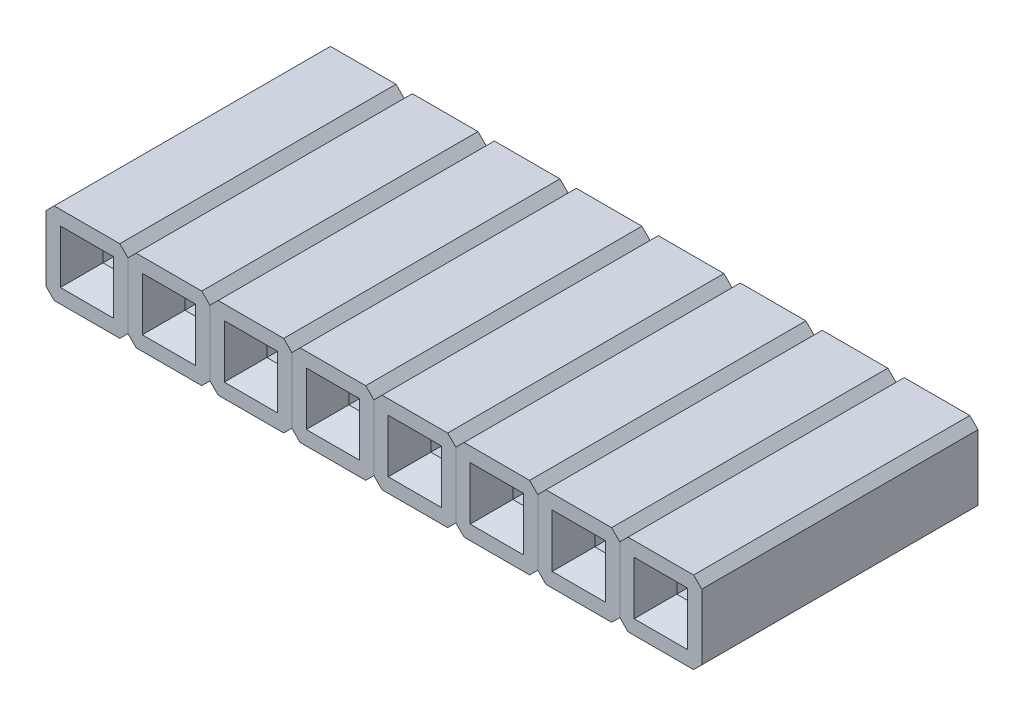
SolidWorks part; units mm, degrees
ref_plane "Front Plane" through (0, 0, 0) normal (0, 0, 1) x (1, 0, 0)
ref_plane "Top Plane" through (0, 0, 0) normal (0, 1, 0) x (1, 0, 0)
ref_plane "Right Plane" through (0, 0, 0) normal (1, 0, 0) x (0, 0, -1)
sketch "Sketch1" plane through (0, 0, 0) normal (0, 0, 1) x (1, 0, 0)
  line L1 (0, 0) -> (2.54, 0)
  line L2 (0, 0) -> (0, 2.54)
  line L3 (0, 2.54) -> (2.54, 2.54)
  line L4 (2.54, 0) -> (2.54, 2.54)
  dimension "D1" = 2.54
  dimension "D2" = 2.54
extrude "Boss-Extrude1" add sketch "Sketch1" along normal blind 8.5598
sketch "Sketch2" plane through (0, 0, 8.5598) normal (0, 0, 1) x (1, 0, 0)
  line L0 (0, 1.27) -> (2.54, 1.27) construction
  line L1 (0, 2.54) -> (0, 0) construction
  line L2 (2.54, 0) -> (2.54, 2.54) construction
  line L4 (0.9525, 0.9525) -> (1.5875, 0.9525)
  line L5 (0.9525, 0.9525) -> (0.9525, 1.5875)
  line L6 (0.9525, 1.5875) -> (1.5875, 1.5875)
  line L7 (1.5875, 0.9525) -> (1.5875, 1.5875)
  line L8 (0.9525, 0.9525) -> (1.5875, 1.5875) construction
  line L9 (0.9525, 1.5875) -> (1.5875, 0.9525) construction
  point P6 (1.27, 1.27)
  dimension "D1" = 0.635
extrude "Cut-Extrude1" cut sketch "Sketch2" against normal blind 6.35
chamfer "Chamfer1" distance 0.508 angle 58 4 edges at (0.9525, 1.27, 8.5598) (1.27, 0.9525, 8.5598) (1.5875, 1.27, 8.5598) (1.27, 1.5875, 8.5598)
chamfer "Chamfer2" distance 0.254 angle 45 4 edges at (0, 2.54, 4.2799) (2.54, 2.54, 4.2799) (2.54, 0, 4.2799) (0, 0, 4.2799)
pattern_linear "LPattern1" count 8 spacing 2.54 along (-1, 0, 0) of bodies 102
